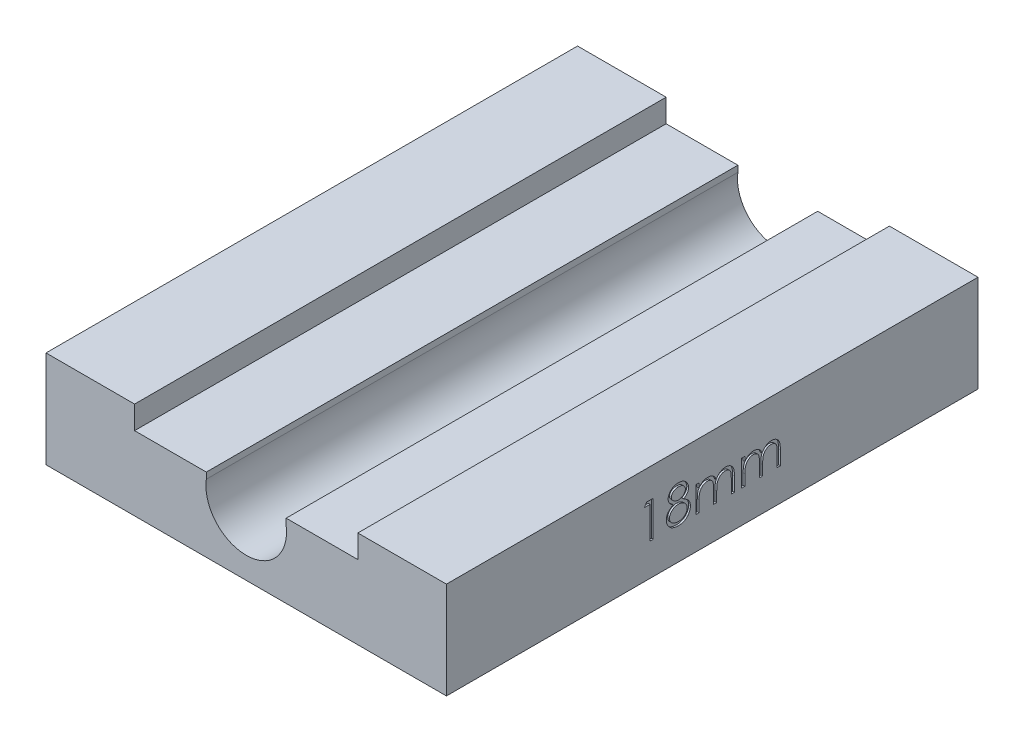
SolidWorks part; units mm, degrees
ref_plane "Front Plane" through (0, 0, 0) normal (0, 0, 1) x (1, 0, 0)
ref_plane "Top Plane" through (0, 0, 0) normal (0, 1, 0) x (1, 0, 0)
ref_plane "Right Plane" through (0, 0, 0) normal (1, 0, 0) x (0, 0, -1)
sketch "Sketch1" plane through (0, 0, 0) normal (0, 0, 1) x (1, 0, 0)
  line L0 (0, 0) -> (0, 12.8693) construction
  line L1 (0, 12.8693) -> (-10, 2.8693)
  line L2 (0, 12.8693) -> (10, 2.8693)
  line L3 (-10, 2.8693) -> (-25, 2.8693)
  line L4 (-25, 2.8693) -> (-25, 22.8693)
  line L5 (-25, 22.8693) -> (25, 22.8693)
  line L6 (25, 22.8693) -> (25, 2.8693)
  line L7 (25, 2.8693) -> (10, 2.8693)
  line L8 (-45.2, 7.8693) -> (-45.2, -14)
  line L9 (-45.2, -14) -> (45.2, -14)
  line L10 (45.2, -14) -> (45.2, 7.8693)
  line L11 (45.2, 7.8693) -> (25.2, 7.8693)
  line L12 (25.2, 7.8693) -> (25.2, 2.6693)
  line L13 (-25.2, 2.6693) -> (-9.0099, 2.6693)
  line L14 (-45.2, 7.8693) -> (-25.2, 7.8693)
  line L15 (-25.2, 7.8693) -> (-25.2, 2.6693)
  line L16 (25.2, 2.6693) -> (9.0099, 2.6693)
  line L17 (-9.0099, 2.6693) -> (-9.0099, 1.2774)
  line L18 (9.0099, 2.6693) -> (9.0099, 1.2774)
  circle A0 centre (0, 0) radius 9.1
  dimension "D12" = 18.2
  dimension "D1" = 45
  dimension "D2" = 10
  dimension "D3" = 20
  dimension "D4" = 50
  dimension "D5" = 25
  dimension "D6" = 5
  dimension "D7" = 0.2
  dimension "D8" = 0.2
  dimension "D9" = 5
  dimension "D10" = 20
  dimension "D11" = 20
  dimension "D13" = 14
  dimension "D14" = 0.2
  dimension "D15" = 0.2
extrude "Boss-Extrude1" add sketch "Sketch1" along normal blind 120 contours A0 L17 L13 L15 L14 L8 L9 L10 L11 L12 L16 L18
sketch "Sketch2" plane through (45.2, 0, 0) normal (1, 0, 0) x (0, 0, -1)
  text T0 "18mm" font "Century Gothic" height 8
extrude "Cut-Extrude1" cut sketch "Sketch2" against normal blind 0.4
